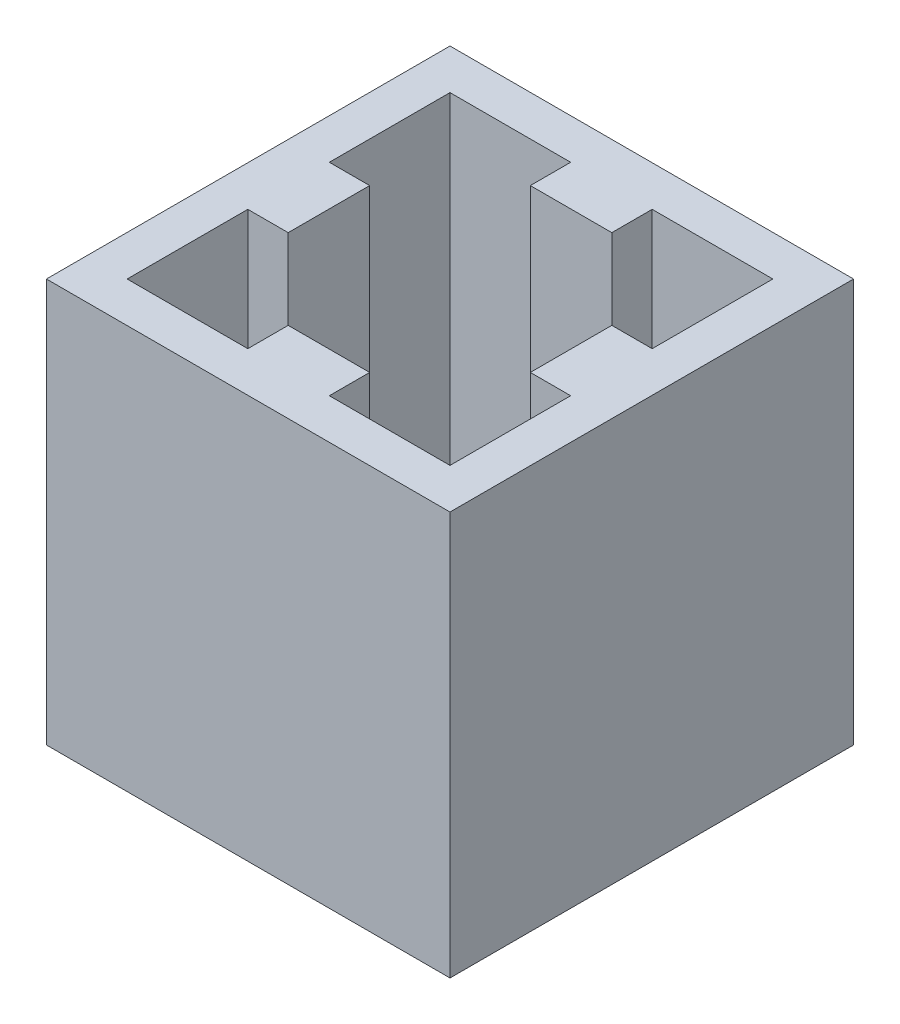
SolidWorks part; units mm, degrees
ref_plane "Front Plane" through (0, 0, 0) normal (0, 0, 1) x (1, 0, 0)
ref_plane "Top Plane" through (0, 0, 0) normal (0, 1, 0) x (1, 0, 0)
ref_plane "Right Plane" through (0, 0, 0) normal (1, 0, 0) x (0, 0, -1)
sketch "Sketch1" plane through (0, 0, 0) normal (0, 1, 0) x (1, 0, 0)
  line L1 (-12.7, -12.7) -> (12.7, -12.7)
  line L2 (-12.7, -12.7) -> (-12.7, 12.7)
  line L3 (-12.7, 12.7) -> (12.7, 12.7)
  line L4 (12.7, -12.7) -> (12.7, 12.7)
  line L5 (-12.7, -12.7) -> (12.7, 12.7) construction
  line L6 (-12.7, 12.7) -> (12.7, -12.7) construction
  point P0 (0, 0)
  dimension "D1" = 25.4
  dimension "D2" = 25.4
extrude "Boss-Extrude1" add sketch "Sketch1" along normal blind 25.4 contours L4 L1 L2 L3
sketch "Sketch3" plane through (0, 25.4, 0) normal (0, 1, 0) x (1, 0, 0)
  line L6 (10.16, 2.5651) -> (7.62, 2.5651)
  line L7 (7.62, 2.5651) -> (7.62, -2.5651)
  line L8 (7.62, -2.5651) -> (10.16, -2.5651)
  line L9 (10.16, 10.16) -> (-10.16, 10.16)
  line L10 (-10.16, 10.16) -> (-10.16, -10.16)
  line L11 (-10.16, -10.16) -> (10.16, -10.16)
  line L12 (10.16, -10.16) -> (10.16, 10.16)
  line L13 (10.16, 10.16) -> (2.5651, 10.16)
  line L14 (-10.16, 10.16) -> (-10.16, 2.5651)
  line L15 (-10.16, -10.16) -> (-2.5651, -10.16)
  line L16 (10.16, -10.16) -> (10.16, -2.5651)
  line L17 (-2.5651, -7.62) -> (-2.5651, -10.16)
  line L19 (2.5651, -10.16) -> (2.5651, -7.62)
  line L20 (2.5651, -7.62) -> (-2.5651, -7.62)
  line L21 (-7.62, 2.5651) -> (-10.16, 2.5651)
  line L23 (-10.16, -2.5651) -> (-7.62, -2.5651)
  line L24 (-7.62, -2.5651) -> (-7.62, 2.5651)
  line L25 (2.5651, 7.62) -> (2.5651, 10.16)
  line L27 (-2.5651, 10.16) -> (-2.5651, 7.62)
  line L28 (-2.5651, 7.62) -> (2.5651, 7.62)
  line L31 (-2.5651, 10.16) -> (-10.16, 10.16)
  line L33 (10.16, 2.5651) -> (10.16, 10.16)
  line L34 (2.5651, -10.16) -> (10.16, -10.16)
  line L35 (-10.16, -2.5651) -> (-10.16, -10.16)
  line L41 (-12.7, -12.7) -> (12.7, 12.7) construction
  line L42 (-12.7, 12.7) -> (12.7, -12.7) construction
  point P0 (0, 0)
  point P3 (0, 0)
  point P24 (0, 0)
  point P27 (0, 0)
  point P28 (0, 0)
  point P32 (0, 0)
  point P33 (0, 0)
  point P34 (0, 0)
  point P35 (0, 0)
  point P36 (0, 0)
  point P37 (0, 0)
  dimension "D2" = 5.1302
  dimension "D3" = 2.54
  dimension "D1" = 2.54
  dimension "D4" = 4
extrude "Cut-Extrude2" cut sketch "Sketch3" against normal blind 22.86
